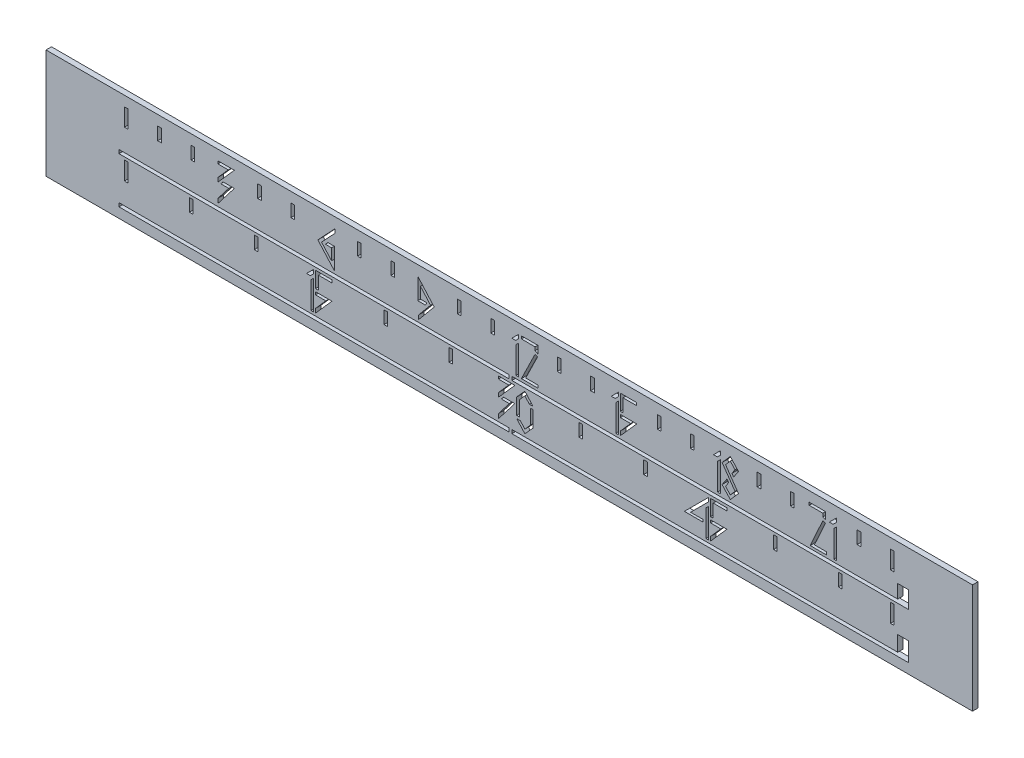
SolidWorks part; units mm, degrees
ref_plane "Спереди" through (0, 0, 0) normal (0, 0, 1) x (1, 0, 0)
ref_plane "Сверху" through (0, 0, 0) normal (0, 1, 0) x (1, 0, 0)
ref_plane "Справа" through (0, 0, 0) normal (1, 0, 0) x (0, 0, -1)
sketch "Sketch1" plane through (0, 0, 0) normal (0, 0, 1) x (1, 0, 0)
  line L1 (0, 0) -> (500, 0)
  line L2 (0, 0) -> (0, 60)
  line L3 (0, 60) -> (500, 60)
  line L4 (500, 0) -> (500, 60)
  dimension "D1" = 500
  dimension "D2" = 60
extrude "Boss-Extrude1" add sketch "Sketch1" along normal blind 3
sketch "Sketch2" plane through (0, 0, 3) normal (0, 0, 1) x (1, 0, 0)
  line L0 (0, 30) -> (500, 30) construction
  line L1 (36, 30.75) -> (195.8279, 30.75)
  line L2 (36, 30.75) -> (36, 32.75)
  line L3 (36, 32.75) -> (191.8279, 32.75)
  line L5 (0, 60) -> (0, 0) construction
  line L6 (500, 0) -> (500, 60) construction
  line L7 (249.7246, 30.75) -> (249.7246, 32.75)
  line L8 (193.3102, 32.75) -> (191.8279, 32.75)
  line L9 (197.3102, 30.75) -> (195.8279, 30.75)
  line L10 (465, 30.75) -> (469, 30.75)
  line L11 (469, 30.75) -> (469, 40.1464)
  line L12 (251.4357, 32.75) -> (251.4357, 30.75)
  line L13 (469, 40.1464) -> (463, 40.1464)
  line L14 (463, 40.1464) -> (463, 32.75)
  line L16 (251.4357, 30.75) -> (465, 30.75)
  line L18 (197.3102, 30.75) -> (249.7246, 30.75)
  line L19 (251.4357, 32.75) -> (463, 32.75)
  line L25 (193.3102, 32.75) -> (249.7246, 32.75)
  dimension "D1" = 36
  dimension "D2" = 429
  dimension "D3" = 30.75
  dimension "D4" = 2
  dimension "D5" = 4
  dimension "D6" = 6
extrude "Hours_hand_Hole" cut sketch "Sketch2" against normal blind 3
sketch "Sketch3" plane through (0, 0, 3) normal (0, 0, 1) x (1, 0, 0)
  line L0 (40, 34.25) -> (460, 34.25) construction
  line L1 (40, 54.5) -> (460, 54.5) construction
  line L2 (500, 60) -> (0, 60) construction
  line L3 (40, 29.25) -> (460, 29.25) construction
  line L4 (40, 9) -> (460, 9) construction
  point P8 (40, 34.25)
  point P10 (58.26, 34.25)
  point P11 (76.52, 34.25)
  point P12 (94.78, 34.25)
  point P13 (113.04, 34.25)
  point P14 (131.3, 34.25)
  point P15 (149.56, 34.25)
  point P16 (167.82, 34.25)
  point P17 (186.08, 34.25)
  point P18 (204.34, 34.25)
  point P19 (222.6, 34.25)
  point P20 (240.86, 34.25)
  point P21 (259.12, 34.25)
  point P22 (277.38, 34.25)
  point P23 (295.64, 34.25)
  point P24 (313.9, 34.25)
  point P25 (332.16, 34.25)
  point P26 (350.42, 34.25)
  point P27 (368.68, 34.25)
  point P28 (386.94, 34.25)
  point P29 (405.2, 34.25)
  point P30 (423.46, 34.25)
  point P31 (441.72, 34.25)
  point P32 (459.98, 34.25)
  point P39 (40, 29.25)
  point P41 (47.1186, 29.25)
  point P42 (54.2373, 29.25)
  point P43 (61.3559, 29.25)
  point P44 (68.4746, 29.25)
  point P45 (75.5932, 29.25)
  point P46 (82.7119, 29.25)
  point P47 (89.8305, 29.25)
  point P48 (96.9492, 29.25)
  point P49 (104.0678, 29.25)
  point P50 (111.1864, 29.25)
  point P51 (118.3051, 29.25)
  point P52 (125.4237, 29.25)
  point P53 (132.5424, 29.25)
  point P54 (139.661, 29.25)
  point P55 (146.7797, 29.25)
  point P56 (153.8983, 29.25)
  point P57 (161.0169, 29.25)
  point P58 (168.1356, 29.25)
  point P59 (175.2542, 29.25)
  point P60 (182.3729, 29.25)
  point P61 (189.4915, 29.25)
  point P62 (196.6102, 29.25)
  point P63 (203.7288, 29.25)
  point P64 (210.8475, 29.25)
  point P65 (217.9661, 29.25)
  point P66 (225.0847, 29.25)
  point P67 (232.2034, 29.25)
  point P68 (239.322, 29.25)
  point P69 (246.4407, 29.25)
  point P70 (253.5593, 29.25)
  point P71 (260.678, 29.25)
  point P72 (267.7966, 29.25)
  point P73 (274.9153, 29.25)
  point P74 (282.0339, 29.25)
  point P75 (289.1525, 29.25)
  point P76 (296.2712, 29.25)
  point P77 (303.3898, 29.25)
  point P78 (310.5085, 29.25)
  point P79 (317.6271, 29.25)
  point P80 (324.7458, 29.25)
  point P81 (331.8644, 29.25)
  point P82 (338.9831, 29.25)
  point P83 (346.1017, 29.25)
  point P84 (353.2203, 29.25)
  point P85 (360.339, 29.25)
  point P86 (367.4576, 29.25)
  point P87 (374.5763, 29.25)
  point P88 (381.6949, 29.25)
  point P89 (388.8136, 29.25)
  point P90 (395.9322, 29.25)
  point P91 (403.0508, 29.25)
  point P92 (410.1695, 29.25)
  point P93 (417.2881, 29.25)
  point P94 (424.4068, 29.25)
  point P95 (431.5254, 29.25)
  point P96 (438.6441, 29.25)
  point P97 (445.7627, 29.25)
  point P98 (452.8814, 29.25)
  point P99 (460, 29.25)
  dimension "D2" = 420
  dimension "D3" = 5.5
  dimension "D4" = 420
  dimension "D6" = 1.5
  dimension "D7" = 420
  dimension "D8" = 20.25
  dimension "D9" = 420
  dimension "D11" = 40
  dimension "D12" = 40
  dimension "D13" = 1.5
  dimension "D5" = 24
  dimension "D10" = 60
sketch "three" plane through (0, 0, 3) normal (0, 0, 1) x (1, 0, 0)
  line L0 (90.28, 54.5) -> (99.28, 54.5)
  line L1 (40, 34.25) -> (460, 34.25) construction
  line L2 (40, 54.5) -> (460, 54.5) construction
  line L3 (99.28, 54.5) -> (90.28, 44.375)
  line L4 (90.28, 34.25) -> (90.28, 54.5) construction
  line L5 (99.28, 34.25) -> (99.28, 54.5) construction
  line L6 (90.28, 53) -> (95.9397, 53)
  line L7 (95.9397, 53) -> (90.28, 46.6328)
  line L8 (90.28, 54.5) -> (90.28, 53)
  line L9 (90.28, 44.375) -> (90.28, 46.6328)
  line L10 (93.1133, 45.875) -> (99.28, 45.875)
  line L11 (95.9397, 53) -> (89.1589, 45.3715) construction
  line L12 (99.28, 45.875) -> (90.28, 34.25)
  line L13 (91.78, 44.375) -> (96.2217, 44.375)
  line L14 (96.2217, 44.375) -> (90.28, 36.7003)
  line L15 (90.28, 34.25) -> (90.28, 36.7003)
  line L16 (91.78, 44.375) -> (93.1133, 45.875)
  line L17 (96.2217, 44.375) -> (89.0939, 35.1683) construction
  line L19 (91.78, 45.875) -> (99.28, 45.875) construction
  dimension "D1" = 1.5
  dimension "D2" = 1.5
  dimension "D3" = 4.5
  dimension "D4" = 4.5
  dimension "D6" = 1.5
  dimension "D5" = 1.5
extrude "Three_cut" cut sketch "three" against normal blind 10
sketch "six" plane through (0, 0, 3) normal (0, 0, 1) x (1, 0, 0)
  line L1 (40, 34.25) -> (460, 34.25) construction
  line L2 (40, 54.5) -> (460, 54.5) construction
  line L4 (154.5826, 54.5) -> (145.06, 44.328)
  line L5 (145.06, 44.328) -> (154.06, 34.25)
  line L6 (154.5826, 52.3052) -> (147.0924, 44.3041)
  line L7 (154.06, 34.25) -> (154.06, 45.828)
  line L8 (147.0924, 44.3041) -> (152.56, 38.1816)
  line L9 (154.06, 45.828) -> (150.5737, 45.828)
  line L10 (152.56, 38.1816) -> (152.56, 44.328)
  line L11 (152.56, 44.328) -> (149.1694, 44.328)
  line L12 (154.5826, 54.5) -> (154.5826, 52.3052)
  line L13 (150.5737, 45.828) -> (149.1694, 44.328)
  line L15 (152.56, 44.328) -> (147.5401, 44.328) construction
  line L16 (154.06, 45.828) -> (147.5401, 45.828) construction
  line L17 (155.6776, 53.4749) -> (147.0924, 44.3041) construction
  point P9 (155.1811, 53.5035)
  point P11 (147.0669, 44.375)
  point P12 (155.1811, 35.2465)
  point P16 (149.56, 45.875)
  dimension "D1" = 9
  dimension "D2" = 4.5
  dimension "D4" = 1.5
  dimension "D6" = 10.172
  dimension "D5" = 1.5
  dimension "D3" = 1.5
extrude "Six_cut" cut sketch "six" against normal blind 10
sketch "nine" plane through (0, 0, 3) normal (0, 0, 1) x (1, 0, 0)
  line L0 (200.3607, 34.1717) -> (208.84, 44.328)
  line L1 (208.84, 44.328) -> (199.84, 54.5)
  line L2 (200.3607, 36.4197) -> (206.8424, 44.1833)
  line L3 (199.84, 54.5) -> (199.84, 42.828)
  line L4 (206.8424, 44.1833) -> (201.34, 50.4022)
  line L5 (199.84, 42.828) -> (204.0297, 42.828)
  line L6 (201.34, 50.4022) -> (201.34, 44.328)
  line L7 (201.34, 44.328) -> (204.8343, 44.328)
  line L8 (200.3607, 34.1717) -> (200.3607, 36.4197)
  line L9 (204.0297, 42.828) -> (204.8343, 44.328)
  line L10 (199.84, 34.25) -> (199.84, 54.5) construction
  line L11 (40, 34.25) -> (460, 34.25) construction
  line L12 (40, 54.5) -> (460, 54.5) construction
  dimension "D1" = 1.4993
  dimension "D2" = 4.5
  dimension "D3" = 11.672
  dimension "D4" = 2.0028
  dimension "D5" = 8.672
  dimension "D6" = 1.5
  dimension "D7" = 9
  dimension "D8" = 3.4943
extrude "Nine_cut" cut sketch "nine" against normal blind 10
sketch "twelve" plane through (0, 0, 3) normal (0, 0, 1) x (1, 0, 0)
  line L0 (255.12, 34.25) -> (255.12, 54.5) construction
  line L1 (40, 34.25) -> (460, 34.25) construction
  line L2 (40, 54.5) -> (460, 54.5) construction
  line L3 (246.12, 34.25) -> (246.12, 54.5) construction
  line L4 (265.6426, 54.594) -> (265.6426, 50.5304)
  line L5 (264.1426, 53.094) -> (264.1426, 51.2636)
  line L6 (264.1426, 49.594) -> (256.6426, 34.25)
  line L7 (255.12, 54.5) -> (255.12, 52.4061)
  line L8 (255.12, 34.25) -> (253.62, 34.25)
  line L9 (255.12, 54.5) -> (251.3711, 50.8487)
  line L10 (251.3711, 50.8487) -> (253.521, 50.8487)
  line L11 (253.62, 48.8513) -> (253.62, 34.25)
  line L12 (255.12, 52.4061) -> (253.521, 50.8487)
  line L13 (255.12, 50.3123) -> (253.62, 48.8513)
  line L14 (255.12, 50.3123) -> (255.12, 34.25)
  line L15 (256.6426, 54.594) -> (265.6426, 54.594)
  line L16 (265.4902, 48.9353) -> (259.0454, 35.75)
  line L17 (264.1426, 53.094) -> (256.6426, 53.094)
  line L18 (256.6426, 53.094) -> (256.6426, 54.594)
  line L19 (265.6426, 34.25) -> (256.6426, 34.25)
  line L20 (265.6426, 35.75) -> (259.0454, 35.75)
  line L21 (264.1426, 49.594) -> (265.4902, 48.9353)
  line L22 (265.6426, 35.75) -> (265.6426, 34.25)
  line L23 (264.1426, 51.2636) -> (265.6426, 50.5304)
  dimension "D2" = 9
  dimension "D3" = 1.5
  dimension "D4" = 1.5
  dimension "D5" = 1.5
  dimension "D6" = 4.0636
  dimension "D7" = 1.5
  dimension "D8" = 1.5
  dimension "D9" = 1.5
  dimension "D10" = 16.2804
  dimension "D11" = 1.5
  dimension "D12" = 14.6013
  dimension "D13" = 1.8304
  dimension "D14" = 4
  dimension "D15" = 9
  dimension "D16" = 9
  dimension "D17" = 18.844
extrude "Twelve_cut" cut sketch "twelve" against normal blind 10
sketch "fifteen" plane through (0, 0, 3) normal (0, 0, 1) x (1, 0, 0)
  line L0 (309.9011, 54.5) -> (309.9011, 52.3787)
  line L1 (309.9011, 34.156) -> (308.4011, 34.156)
  line L2 (309.9011, 54.5) -> (305.9462, 50.5451)
  line L3 (305.9462, 50.5451) -> (308.0675, 50.5451)
  line L4 (308.4011, 48.7574) -> (308.4011, 34.156)
  line L5 (309.9011, 52.3787) -> (308.0675, 50.5451)
  line L6 (309.9011, 50.2574) -> (308.4011, 48.7574)
  line L7 (309.9011, 50.2574) -> (309.9011, 34.156)
  line L10 (40, 54.5) -> (460, 54.5) construction
  line L11 (310.8967, 34.25) -> (310.8967, 54.5) construction
  line L12 (40, 34.25) -> (460, 34.25) construction
  line L13 (319.8967, 34.25) -> (319.8967, 54.5) construction
  line L14 (310.8967, 34.25) -> (319.8967, 44.375)
  line L15 (319.8967, 44.375) -> (310.8967, 44.375)
  line L16 (310.8967, 36.5078) -> (316.5564, 42.875)
  line L17 (316.5564, 42.875) -> (310.8967, 42.875)
  line L18 (310.8967, 34.25) -> (310.8967, 36.5078)
  line L19 (310.8967, 44.375) -> (310.8967, 42.875)
  line L20 (319.8967, 54.5) -> (310.8967, 54.5)
  line L21 (309.7756, 35.2465) -> (316.5564, 42.875) construction
  line L22 (310.8967, 54.5) -> (310.8967, 45.875)
  line L23 (310.8967, 45.875) -> (312.3967, 45.875)
  line L24 (312.3967, 45.875) -> (312.3967, 53)
  line L25 (312.3967, 53) -> (319.8967, 53)
  line L26 (319.8967, 53) -> (319.8967, 54.5)
  dimension "D1" = 1.5
  dimension "D2" = 1.5
  dimension "D3" = 16.1013
  dimension "D4" = 2.1213
  dimension "D5" = 2.1213
  dimension "D6" = 5.5931
  dimension "D7" = 14.6013
  dimension "D8" = 4
  dimension "D9" = 1
  dimension "D10" = 9
  dimension "D12" = 1.5
  dimension "D13" = 1.5
  dimension "D14" = 1.5
  dimension "D11" = 1.5
extrude "Fifteen_cut" cut sketch "fifteen" against normal blind 10
sketch "eighteen" plane through (0, 0, 3) normal (0, 0, 1) x (1, 0, 0)
  line L0 (40, 54.5) -> (460, 54.5) construction
  line L1 (369.9526, 34.25) -> (369.9526, 54.5) construction
  line L2 (40, 34.25) -> (460, 34.25) construction
  line L3 (378.9526, 34.25) -> (378.9526, 54.5) construction
  line L7 (365.6815, 54.5) -> (365.6815, 52.3787)
  line L8 (365.6815, 34.156) -> (364.1815, 34.156)
  line L9 (365.6815, 54.5) -> (361.9871, 50.8056)
  line L10 (361.9871, 50.8056) -> (364.1084, 50.8056)
  line L11 (364.1815, 48.7574) -> (364.1815, 34.156)
  line L12 (365.6815, 52.3787) -> (364.1084, 50.8056)
  line L13 (365.6815, 50.2574) -> (364.1815, 48.7574)
  line L14 (365.6815, 50.2574) -> (365.6815, 34.156)
  line L23 (375.6878, 49.6794) -> (371.1705, 54.5708)
  line L24 (371.1705, 54.5708) -> (366.6866, 49.4629)
  line L25 (373.7828, 39.2945) -> (366.6866, 49.4629)
  line L26 (368.5897, 49.3571) -> (375.6866, 39.1875)
  line L27 (375.6866, 39.1875) -> (371.1982, 34.086)
  line L28 (371.1982, 34.086) -> (366.6815, 38.9766)
  line L29 (366.6815, 38.9766) -> (369.3778, 42.9855)
  line L31 (373.7815, 49.5327) -> (371.1988, 52.3292)
  line L32 (371.1988, 52.3292) -> (368.5897, 49.3571)
  line L35 (373.7828, 39.2945) -> (371.1711, 36.3261)
  line L36 (371.1711, 36.3261) -> (368.5878, 39.1233)
  line L37 (368.5878, 39.1233) -> (370.2983, 41.6664)
  line L38 (372.071, 46.9896) -> (372.9915, 45.6705)
  line L41 (369.3778, 42.9855) -> (370.2983, 41.6664)
  line L42 (372.071, 46.9896) -> (373.7815, 49.5327)
  line L43 (372.9915, 45.6705) -> (375.6878, 49.6794)
  point P24 (374.464, 43.0011)
  point P32 (374.4412, 45.6549)
  point P36 (374.4412, 45.6549)
  point P40 (374.464, 43.0011)
  dimension "D2" = 2.1213
  dimension "D3" = 1.5
  dimension "D4" = 1.5
  dimension "D5" = 1.5
  dimension "D6" = 16.1013
  dimension "D7" = 3
  dimension "D8" = 1
  dimension "D9" = 9
  dimension "D10" = 6.795
  dimension "D11" = 6.6573
  dimension "D12" = 14.6013
  dimension "D13" = 4.8313
  dimension "D14" = 12.401
  dimension "D15" = 12.3997
  dimension "D16" = 6.6582
  dimension "D17" = 6.7967
  dimension "D18" = 5.1949
  dimension "D19" = 5.1918
  dimension "D20" = 84.002
  dimension "D22" = 10.4918
  dimension "D23" = 1.0052
  dimension "D21" = 84.065
  dimension "D24" = 1.5
  dimension "D25" = 1.5
  dimension "D26" = 1.5
  dimension "D27" = 1.5
  dimension "D28" = 1.5
  dimension "D29" = 1.5
  dimension "D30" = 1.5
  dimension "D31" = 8.9002
extrude "Eighteen_cut" cut sketch "eighteen" against normal blind 10
sketch "twenty_one" plane through (0, 0, 3) normal (0, 0, 1) x (1, 0, 0)
  line L0 (423.46, 54.5) -> (423.46, 50.4655)
  line L1 (421.9138, 53) -> (421.9138, 51.169)
  line L2 (421.96, 49.5) -> (414.9822, 34.1627)
  line L3 (414.46, 54.5) -> (423.46, 54.5)
  line L4 (423.3253, 48.8788) -> (417.3126, 35.6627)
  line L5 (421.9138, 53) -> (414.46, 53)
  line L6 (414.46, 53) -> (414.46, 54.5)
  line L7 (423.9822, 34.1627) -> (414.9822, 34.1627)
  line L8 (423.9822, 35.6627) -> (417.3126, 35.6627)
  line L9 (421.96, 49.5) -> (423.3253, 48.8788)
  line L10 (423.9822, 35.6627) -> (423.9822, 34.1627)
  line L11 (421.9138, 51.169) -> (423.46, 50.4655)
  line L14 (40, 54.5) -> (460, 54.5) construction
  line L15 (429.4149, 54.5) -> (429.4149, 52.3787)
  line L16 (429.4149, 34.156) -> (427.9149, 34.156)
  line L17 (429.4149, 54.5) -> (425.46, 50.5451)
  line L18 (425.46, 50.5451) -> (427.5813, 50.5451)
  line L19 (427.9149, 48.7574) -> (427.9149, 34.156)
  line L20 (429.4149, 52.3787) -> (427.5813, 50.5451)
  line L21 (429.4149, 50.2574) -> (427.9149, 48.7574)
  line L22 (429.4149, 50.2574) -> (429.4149, 34.156)
  dimension "D2" = 9
  dimension "D3" = 9
  dimension "D4" = 1.5
  dimension "D5" = 1.5
  dimension "D6" = 1.5
  dimension "D7" = 20.344
  dimension "D8" = 1.6696
  dimension "D9" = 2
  dimension "D10" = 2.1213
  dimension "D11" = 1.5
  dimension "D12" = 2.1213
  dimension "D13" = 16.1013
  dimension "D14" = 14.6013
  dimension "D15" = 1.5
  dimension "D16" = 5.5931
  dimension "D17" = 2
  dimension "D18" = 1.5
  dimension "D19" = 3.5
  dimension "D20" = 7.5
extrude "Twenty_One_cut" cut sketch "twenty_one" against normal blind 10
sketch "Sketch4" plane through (0, 0, 3) normal (0, 0, 1) x (1, 0, 0)
  line L0 (142.7797, 29.25) -> (142.7797, 27.1287)
  line L1 (142.7797, 8.906) -> (141.2797, 8.906)
  line L2 (142.7797, 29.25) -> (138.8247, 25.2951)
  line L3 (138.8247, 25.2951) -> (140.9461, 25.2951)
  line L4 (141.2797, 23.5074) -> (141.2797, 8.906)
  line L5 (142.7797, 27.1287) -> (140.9461, 25.2951)
  line L6 (142.7797, 25.0074) -> (141.2797, 23.5074)
  line L7 (142.7797, 25.0074) -> (142.7797, 8.906)
  line L8 (40, 29.25) -> (460, 29.25) construction
  line L11 (143.7797, 8.906) -> (143.7797, 29.25) construction
  line L13 (152.7797, 8.906) -> (152.7797, 29.25) construction
  line L14 (143.7797, 8.906) -> (152.7797, 19.078)
  line L15 (152.7797, 19.078) -> (143.7797, 19.078)
  line L16 (143.7797, 11.1697) -> (149.4496, 17.578)
  line L17 (149.4496, 17.578) -> (143.7797, 17.578)
  line L18 (143.7797, 8.906) -> (143.7797, 11.1697)
  line L19 (143.7797, 19.078) -> (143.7797, 17.578)
  line L20 (152.7797, 29.25) -> (143.7797, 29.25)
  line L21 (142.6563, 9.9) -> (149.4496, 17.578) construction
  line L22 (143.7797, 29.25) -> (143.7797, 20.578)
  line L23 (143.7797, 20.578) -> (145.2797, 20.578)
  line L24 (145.2797, 20.578) -> (145.2797, 27.75)
  line L25 (145.2797, 27.75) -> (152.7797, 27.75)
  line L26 (152.7797, 27.75) -> (152.7797, 29.25)
  dimension "D1" = 1.5
  dimension "D2" = 1.5
  dimension "D3" = 16.1013
  dimension "D4" = 2.1213
  dimension "D5" = 2.1213
  dimension "D6" = 5.5931
  dimension "D7" = 14.6013
  dimension "D8" = 2.1213
  dimension "D9" = 1
  dimension "D10" = 9
  dimension "D12" = 1.5
  dimension "D13" = 1.5
  dimension "D14" = 1.5
  dimension "D15" = 1
  dimension "D16" = 3
  dimension "D11" = 1.5
extrude "Cut-Extrude9" cut sketch "Sketch4" against normal blind 10
sketch "forty_five" plane through (0, 0, 3) normal (0, 0, 1) x (1, 0, 0)
  line L0 (359.339, 29.25) -> (359.339, 27.1287)
  line L1 (359.339, 8.906) -> (357.839, 8.906)
  line L2 (356.339, 17.1999) -> (349.4102, 17.1999)
  line L3 (359.339, 27.1287) -> (349.4102, 17.1999)
  line L4 (357.839, 23.5074) -> (357.839, 8.906)
  line L6 (359.339, 25.0074) -> (357.839, 23.5074)
  line L7 (359.339, 25.0074) -> (359.339, 8.906)
  line L10 (40, 29.25) -> (460, 29.25) construction
  line L11 (360.339, 8.906) -> (360.339, 29.25) construction
  line L12 (359.339, 29.25) -> (346.0044, 15.9154)
  line L13 (369.339, 8.906) -> (369.339, 29.25) construction
  line L14 (360.339, 8.906) -> (369.339, 19.078)
  line L15 (369.339, 19.078) -> (360.339, 19.078)
  line L16 (360.339, 11.1697) -> (366.009, 17.578)
  line L17 (366.009, 17.578) -> (360.339, 17.578)
  line L18 (360.339, 8.906) -> (360.339, 11.1697)
  line L19 (360.339, 19.078) -> (360.339, 17.578)
  line L20 (369.339, 29.25) -> (360.339, 29.25)
  line L21 (359.2156, 9.9) -> (366.009, 17.578) construction
  line L22 (360.339, 29.25) -> (360.339, 20.578)
  line L23 (360.339, 20.578) -> (361.839, 20.578)
  line L24 (361.839, 20.578) -> (361.839, 27.75)
  line L25 (361.839, 27.75) -> (369.339, 27.75)
  line L26 (369.339, 27.75) -> (369.339, 29.25)
  line L27 (346.0044, 15.9154) -> (356.339, 15.9154)
  line L33 (356.339, 17.1999) -> (356.339, 15.9154)
  dimension "D1" = 1.5
  dimension "D2" = 1.5
  dimension "D3" = 16.1013
  dimension "D4" = 2.1213
  dimension "D5" = 2.1213
  dimension "D6" = 1.5
  dimension "D7" = 14.6013
  dimension "D8" = 2.1213
  dimension "D9" = 1
  dimension "D10" = 9
  dimension "D12" = 1.5
  dimension "D13" = 1.5
  dimension "D14" = 1.5
  dimension "D15" = 1
  dimension "D16" = 0
  dimension "D17" = 1.5
  dimension "D18" = 10.3346
  dimension "D11" = 1.5
extrude "Cut-Extrude11" cut sketch "forty_five" against normal blind 10
sketch "Sketch6" plane through (0, 0, 3) normal (0, 0, 1) x (1, 0, 0)
  line L17 (18.7965, 44.375) -> (144.6248, 44.375) construction
  line L18 (440.72, 47.5) -> (440.72, 54.5)
  line L19 (442.72, 47.5) -> (440.72, 47.5)
  line L20 (442.72, 54.5) -> (442.72, 47.5)
  line L29 (440.72, 54.5) -> (442.72, 54.5)
  line L30 (404.2, 47.5) -> (404.2, 54.5)
  line L31 (406.2, 47.5) -> (404.2, 47.5)
  line L32 (406.2, 54.5) -> (406.2, 47.5)
  line L41 (404.2, 54.5) -> (406.2, 54.5)
  line L42 (385.94, 47.5) -> (385.94, 54.5)
  line L43 (387.94, 47.5) -> (385.94, 47.5)
  line L44 (387.94, 54.5) -> (387.94, 47.5)
  line L53 (385.94, 54.5) -> (387.94, 54.5)
  line L54 (349.42, 47.5) -> (349.42, 54.5)
  line L55 (351.42, 47.5) -> (349.42, 47.5)
  line L56 (351.42, 54.5) -> (351.42, 47.5)
  line L65 (349.42, 54.5) -> (351.42, 54.5)
  line L66 (331.16, 47.5) -> (331.16, 54.5)
  line L67 (333.16, 47.5) -> (331.16, 47.5)
  line L68 (333.16, 54.5) -> (333.16, 47.5)
  line L77 (331.16, 54.5) -> (333.16, 54.5)
  line L78 (294.64, 47.5) -> (294.64, 54.5)
  line L79 (296.64, 47.5) -> (294.64, 47.5)
  line L80 (296.64, 54.5) -> (296.64, 47.5)
  line L89 (294.64, 54.5) -> (296.64, 54.5)
  line L90 (276.38, 47.5) -> (276.38, 54.5)
  line L91 (278.38, 47.5) -> (276.38, 47.5)
  line L92 (278.38, 54.5) -> (278.38, 47.5)
  line L125 (276.38, 54.5) -> (278.38, 54.5)
  line L126 (239.86, 47.5) -> (239.86, 54.5)
  line L127 (241.86, 47.5) -> (239.86, 47.5)
  line L128 (241.86, 54.5) -> (241.86, 47.5)
  line L129 (239.86, 54.5) -> (241.86, 54.5)
  line L130 (221.6, 47.5) -> (221.6, 54.5)
  line L131 (223.6, 47.5) -> (221.6, 47.5)
  line L132 (223.6, 54.5) -> (223.6, 47.5)
  line L133 (221.6, 54.5) -> (223.6, 54.5)
  line L134 (185.08, 47.5) -> (185.08, 54.5)
  line L135 (187.08, 47.5) -> (185.08, 47.5)
  line L136 (187.08, 54.5) -> (187.08, 47.5)
  line L137 (185.08, 54.5) -> (187.08, 54.5)
  line L138 (166.82, 47.5) -> (166.82, 54.5)
  line L139 (168.82, 47.5) -> (166.82, 47.5)
  line L140 (168.82, 54.5) -> (168.82, 47.5)
  line L141 (166.82, 54.5) -> (168.82, 54.5)
  line L142 (130.3, 47.5) -> (130.3, 54.5)
  line L143 (132.3, 47.5) -> (130.3, 47.5)
  line L144 (132.3, 54.5) -> (132.3, 47.5)
  line L145 (130.3, 54.5) -> (132.3, 54.5)
  line L146 (112.04, 47.5) -> (112.04, 54.5)
  line L147 (114.04, 47.5) -> (112.04, 47.5)
  line L148 (114.04, 54.5) -> (114.04, 47.5)
  line L149 (112.04, 54.5) -> (114.04, 54.5)
  line L150 (75.52, 47.5) -> (75.52, 54.5)
  line L151 (77.52, 47.5) -> (75.52, 47.5)
  line L152 (77.52, 54.5) -> (77.52, 47.5)
  line L153 (75.52, 54.5) -> (77.52, 54.5)
  line L154 (57.26, 47.5) -> (57.26, 54.5)
  line L155 (59.26, 47.5) -> (57.26, 47.5)
  line L156 (59.26, 54.5) -> (59.26, 47.5)
  line L157 (57.26, 54.5) -> (59.26, 54.5)
  line L158 (460.9981, 44.594) -> (460.9981, 54.5616)
  line L159 (458.9981, 44.594) -> (460.9981, 44.594)
  line L160 (458.9981, 54.5) -> (458.9981, 44.594)
  line L161 (458.9981, 54.5) -> (460.9981, 54.5616)
  line L162 (41, 44.8187) -> (41, 54.5)
  line L163 (39, 44.8187) -> (41, 44.8187)
  line L164 (39, 54.5) -> (39, 44.8187)
  line L165 (41, 54.5) -> (39, 54.5)
  dimension "D3" = 10.125
extrude "Cut-Extrude12" cut sketch "Sketch6" against normal blind 10
sketch "Sketch7" plane through (0, 0, 3) normal (0, 0, 1) x (1, 0, 0)
  line L0 (41, 29.25) -> (39, 29.25)
  line L1 (40, 29.25) -> (460, 29.25) construction
  line L2 (39, 29.25) -> (39, 19.25)
  line L3 (39, 19.25) -> (41, 19.25)
  line L4 (41, 19.25) -> (41, 29.25)
  line L5 (74.5932, 29.25) -> (76.5932, 29.25)
  line L6 (76.5932, 29.25) -> (76.5932, 22.25)
  line L7 (76.5932, 22.25) -> (74.5932, 22.25)
  line L8 (74.5932, 22.25) -> (74.5932, 29.25)
  line L9 (110.1832, 29.25) -> (112.1832, 29.25)
  line L10 (112.1832, 29.25) -> (112.1832, 22.25)
  line L11 (112.1832, 22.25) -> (110.1832, 22.25)
  line L12 (110.1832, 22.25) -> (110.1832, 29.25)
  line L13 (459, 29.25) -> (461, 29.25)
  line L14 (461, 29.25) -> (461, 19.25)
  line L15 (461, 19.25) -> (459, 19.25)
  line L16 (459, 19.25) -> (459, 29.25)
  line L17 (181.3632, 29.25) -> (183.3632, 29.25)
  line L18 (183.3632, 29.25) -> (183.3632, 22.25)
  line L19 (183.3632, 22.25) -> (181.3632, 22.25)
  line L20 (181.3632, 22.25) -> (181.3632, 29.25)
  line L21 (216.9532, 29.25) -> (218.9532, 29.25)
  line L22 (218.9532, 29.25) -> (218.9532, 22.25)
  line L23 (218.9532, 22.25) -> (216.9532, 22.25)
  line L24 (216.9532, 22.25) -> (216.9532, 29.25)
  line L29 (288.1332, 29.25) -> (290.1332, 29.25)
  line L30 (290.1332, 29.25) -> (290.1332, 22.25)
  line L31 (290.1332, 22.25) -> (288.1332, 22.25)
  line L32 (288.1332, 22.25) -> (288.1332, 29.25)
  line L33 (323.7232, 29.25) -> (325.7232, 29.25)
  line L34 (325.7232, 29.25) -> (325.7232, 22.25)
  line L35 (325.7232, 22.25) -> (323.7232, 22.25)
  line L36 (323.7232, 22.25) -> (323.7232, 29.25)
  line L41 (394.9032, 29.25) -> (396.9032, 29.25)
  line L42 (396.9032, 29.25) -> (396.9032, 22.25)
  line L43 (396.9032, 22.25) -> (394.9032, 22.25)
  line L44 (394.9032, 22.25) -> (394.9032, 29.25)
  line L45 (430.4932, 29.25) -> (432.4932, 29.25)
  line L46 (432.4932, 29.25) -> (432.4932, 22.25)
  line L47 (432.4932, 22.25) -> (430.4932, 22.25)
  line L48 (430.4932, 22.25) -> (430.4932, 29.25)
  line L49 (145.7732, 29.25) -> (147.7732, 29.25) [skipped]
  line L50 (147.7732, 29.25) -> (147.7732, 22.25) [skipped]
  line L51 (147.7732, 22.25) -> (145.7732, 22.25) [skipped]
  line L52 (145.7732, 22.25) -> (145.7732, 29.25) [skipped]
  line L53 (252.5432, 29.25) -> (254.5432, 29.25) [skipped]
  line L54 (254.5432, 29.25) -> (254.5432, 22.25) [skipped]
  line L55 (254.5432, 22.25) -> (252.5432, 22.25) [skipped]
  line L56 (252.5432, 22.25) -> (252.5432, 29.25) [skipped]
  line L57 (359.3132, 29.25) -> (361.3132, 29.25) [skipped]
  line L58 (361.3132, 29.25) -> (361.3132, 22.25) [skipped]
  line L59 (361.3132, 22.25) -> (359.3132, 22.25) [skipped]
  line L60 (359.3132, 22.25) -> (359.3132, 29.25) [skipped]
  dimension "D1" = 2
  dimension "D2" = 1
  dimension "D3" = 10
  dimension "D4" = 2
  dimension "D5" = 1
  dimension "D6" = 7
  dimension "D8" = 2
  dimension "D9" = 1
  dimension "D10" = 10
  dimension "D7" = 11
extrude "Cut-Extrude13" cut sketch "Sketch7" against normal blind 10
sketch "Sketch8" plane through (0, 60, 0) normal (0, 1, 0) x (1, 0, 0)
  line L1 (0, 0) -> (-4, 0)
  line L2 (0, 0) -> (0, -3)
  line L3 (0, -3) -> (-4, -3)
  line L4 (-4, 0) -> (-4, -3)
  line L5 (500, 0) -> (504, 0)
  line L6 (500, 0) -> (500, -3)
  line L7 (500, -3) -> (504, -3)
  line L8 (504, 0) -> (504, -3)
  dimension "D1" = 4
  dimension "D2" = 4
  dimension "D3" = 3
  dimension "D4" = 3
extrude "Boss-Extrude2" add sketch "Sketch8" against normal blind 60
sketch "Sketch9" plane through (0, 0, 3) normal (0, 0, 1) x (1, 0, 0)
  line L0 (244.0593, 29.25) -> (253.0593, 29.25)
  line L1 (253.0593, 29.25) -> (244.0593, 19.078)
  line L2 (244.0593, 8.906) -> (244.0593, 29.25) construction
  line L3 (253.0593, 8.906) -> (253.0593, 29.25) construction
  line L4 (244.0593, 27.75) -> (249.7293, 27.75)
  line L5 (249.7293, 27.75) -> (244.0593, 21.3417)
  line L6 (244.0593, 29.25) -> (244.0593, 27.75)
  line L7 (244.0593, 19.078) -> (244.0593, 21.3417)
  line L8 (246.8865, 20.578) -> (253.0593, 20.578)
  line L9 (253.0593, 20.578) -> (244.0593, 8.906)
  line L10 (245.5593, 19.078) -> (250.0086, 19.078)
  line L11 (250.0086, 19.078) -> (244.0593, 11.3625)
  line L12 (244.0593, 8.906) -> (244.0593, 11.3625)
  line L13 (245.5593, 19.078) -> (246.8865, 20.578)
  line L14 (40, 29.25) -> (460, 29.25) construction
  line L15 (254.0593, 29.25) -> (254.0593, 9) construction
  line L16 (40, 9) -> (460, 9) construction
  line L17 (263.0593, 29.25) -> (263.0593, 9) construction
  line L18 (258.5593, 29.25) -> (254.0593, 24.25)
  line L19 (254.0593, 24.25) -> (254.0593, 15.5)
  line L20 (258.5593, 9) -> (254.0593, 14)
  line L21 (258.5593, 29.25) -> (258.5593, 8.5916) construction
  line L22 (258.5593, 9) -> (263.0593, 14)
  line L23 (263.0593, 22.75) -> (263.0593, 14)
  line L24 (258.5593, 29.25) -> (263.0593, 24.25)
  line L25 (258.5593, 27.0077) -> (255.5593, 23.6744)
  line L26 (255.5593, 23.6744) -> (255.5593, 15.5)
  line L27 (258.5593, 11.2423) -> (256.0774, 14)
  line L28 (258.5593, 11.2423) -> (261.5593, 14.5756)
  line L29 (261.5593, 22.75) -> (261.5593, 14.5756)
  line L30 (258.5593, 27.0077) -> (261.0413, 24.25)
  line L31 (263.0593, 24.25) -> (261.0413, 24.25)
  line L32 (263.0593, 22.75) -> (261.5593, 22.75)
  line L33 (254.0593, 14) -> (256.0774, 14)
  line L34 (263.0593, 24.25) -> (263.0593, 14) construction
  line L35 (258.5593, 27.0077) -> (261.5593, 23.6744) construction
  line L36 (261.5593, 23.6744) -> (261.5593, 14.5756) construction
  line L37 (254.0593, 15.5) -> (255.5593, 15.5)
  line L39 (255.5593, 23.6744) -> (255.5593, 14.5756) construction
  line L40 (258.5593, 11.2423) -> (255.5593, 14.5756) construction
  line L41 (254.0593, 24.25) -> (254.0593, 14) construction
  dimension "D1" = 1.5
  dimension "D2" = 20.344
  dimension "D3" = 9
  dimension "D4" = 0.5
  dimension "D5" = 0.5
  dimension "D6" = 9
  dimension "D7" = 4.5
  dimension "D8" = 5
  dimension "D9" = 5
  dimension "D11" = 1.5
  dimension "D12" = 1.5
  dimension "D10" = 1.5
extrude "Cut-Extrude14" cut sketch "Sketch9" against normal blind 10
sketch "Sketch10" plane through (0, 0, 3) normal (0, 0, 1) x (1, 0, 0)
  line L0 (36, 5.5) -> (195.8279, 5.5)
  line L1 (36, 5.5) -> (36, 7.5)
  line L2 (36, 7.5) -> (191.8279, 7.5)
  line L3 (249.7246, 5.5) -> (249.7246, 7.5)
  line L4 (193.3102, 7.5) -> (191.8279, 7.5)
  line L5 (197.3102, 5.5) -> (195.8279, 5.5)
  line L6 (465, 5.5) -> (469, 5.5)
  line L7 (469, 5.5) -> (469, 15.9004)
  line L8 (251.4357, 7.5) -> (251.4357, 5.5)
  line L9 (469, 15.9004) -> (463, 15.9004)
  line L10 (463, 15.9004) -> (463, 7.5)
  line L11 (251.4357, 5.5) -> (465, 5.5)
  line L12 (197.3102, 5.5) -> (249.7246, 5.5)
  line L13 (251.4357, 7.5) -> (463, 7.5)
  line L14 (193.3102, 7.5) -> (249.7246, 7.5)
  line L15 (469, 30.75) -> (469, 40.1464) construction
  line L16 (40, 9) -> (460, 9) construction
  dimension "D1" = 429
  dimension "D2" = 2
  dimension "D3" = 4
  dimension "D4" = 6
  dimension "D5" = 1.5
extrude "Cut-Extrude15" cut sketch "Sketch10" against normal blind 10
